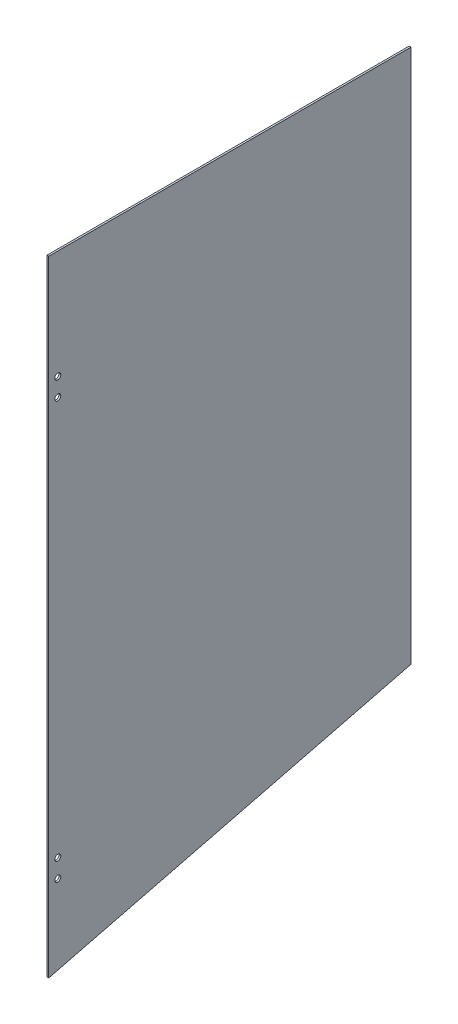
SolidWorks part; units mm, degrees
ref_plane "Front Plane" through (0, 0, 0) normal (0, 0, 1) x (1, 0, 0)
ref_plane "Top Plane" through (0, 0, 0) normal (0, 1, 0) x (1, 0, 0)
ref_plane "Right Plane" through (0, 0, 0) normal (1, 0, 0) x (0, 0, -1)
sketch "Sketch1" plane through (0, 0, 0) normal (1, 0, 0) x (0, 0, -1)
  line L0 (-100, -172.5) -> (100, -122.5)
  line L1 (-100, -172.5) -> (100, -172.5)
  line L2 (-100, -172.5) -> (-100, 172.5)
  line L3 (-100, 172.5) -> (100, 172.5)
  line L4 (100, -172.5) -> (100, 172.5)
  line L5 (-100, -172.5) -> (100, 172.5) construction
  line L6 (-100, 172.5) -> (100, -172.5) construction
  point P0 (0, 0)
  dimension "D1" = 200
  dimension "D2" = 345
  dimension "D3" = 50
extrude "Boss-Extrude1" add sketch "Sketch1" along normal blind 1 contours L0 L4 L3 L2
hole_wizard "M4x0.7 Tapped Hole1" positions "Sketch2" profile "Sketch3" tap size "M4x0.7" standard "ANSI Metric" end condition through all
sketch "Sketch2" plane through (1, 0, 0) normal (1, 0, 0) x (0, 0, -1)
  line L0 (-95, 112.5) -> (-95, 102.5)
  line L2 (-100, -172.5) -> (-100, 172.5) construction
  point P1 (-95, 112.5)
  point P2 (-95, 102.5)
  point P6 (-95, 107.5)
  point P30 (-95, -117.5)
  point P31 (-95, -127.5)
  dimension "D1" = 10
  dimension "D2" = 5
  dimension "D3" = 65
  dimension "D4" = 2
sketch "Sketch3" plane through (1, 112.5, 95) normal (0, 1, 0) x (0, 0, -1)
  line L0 (0, 0) -> (0, 1)
  line L1 (0, 1) -> (1.65, 1)
  line L2 (1.65, 1) -> (1.65, 0)
  line L5 (1.65, 0) -> (0, 0)
  line L11 (0, -6.35) -> (0, 107.95) construction
  dimension "Thru Tap Drill Dia." = 3.3
  dimension "Thru Tap Drill Depth" = 1
cosmetic thread "Hole Thread1" parameters "D2"=4
cosmetic thread "Hole Thread2" parameters "D2"=4
cosmetic thread "Hole Thread3" parameters "D2"=4
cosmetic thread "Hole Thread4" parameters "D2"=4
